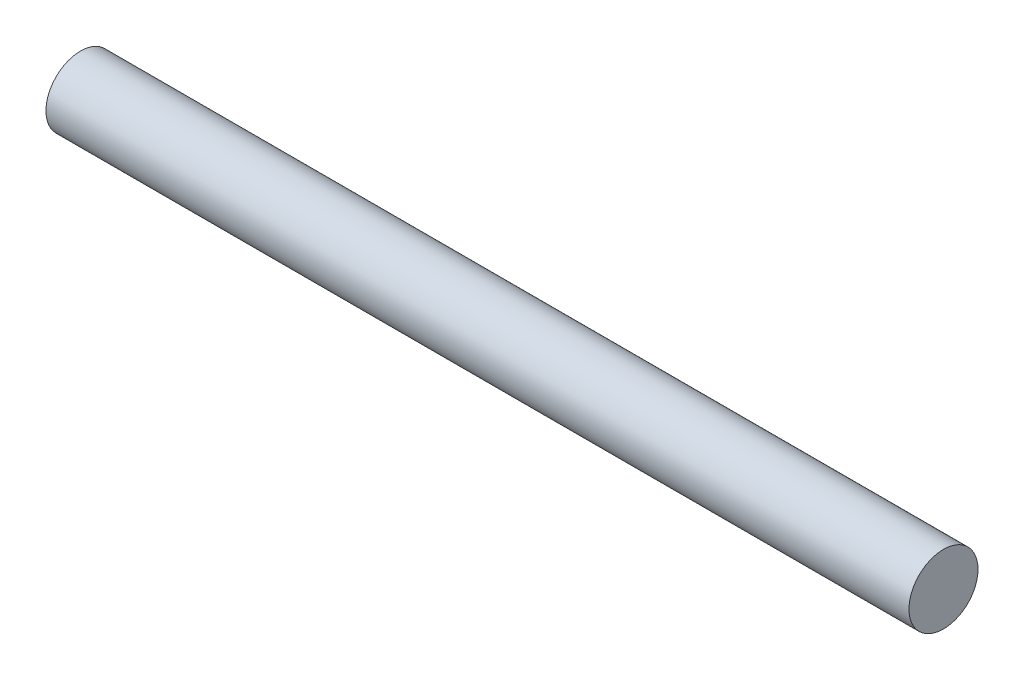
SolidWorks part; units mm, degrees
ref_plane "Front Plane" through (0, 0, 0) normal (0, 0, 1) x (1, 0, 0)
ref_plane "Top Plane" through (0, 0, 0) normal (0, 1, 0) x (1, 0, 0)
ref_plane "Right Plane" through (0, 0, 0) normal (1, 0, 0) x (0, 0, -1)
sketch "Sketch1" plane through (0, 0, 0) normal (1, 0, 0) x (0, 0, -1)
  circle A0 centre (0, 0) radius 4
  dimension "D1" = 8
extrude "Boss-Extrude1" add sketch "Sketch1" along normal mid plane 100
